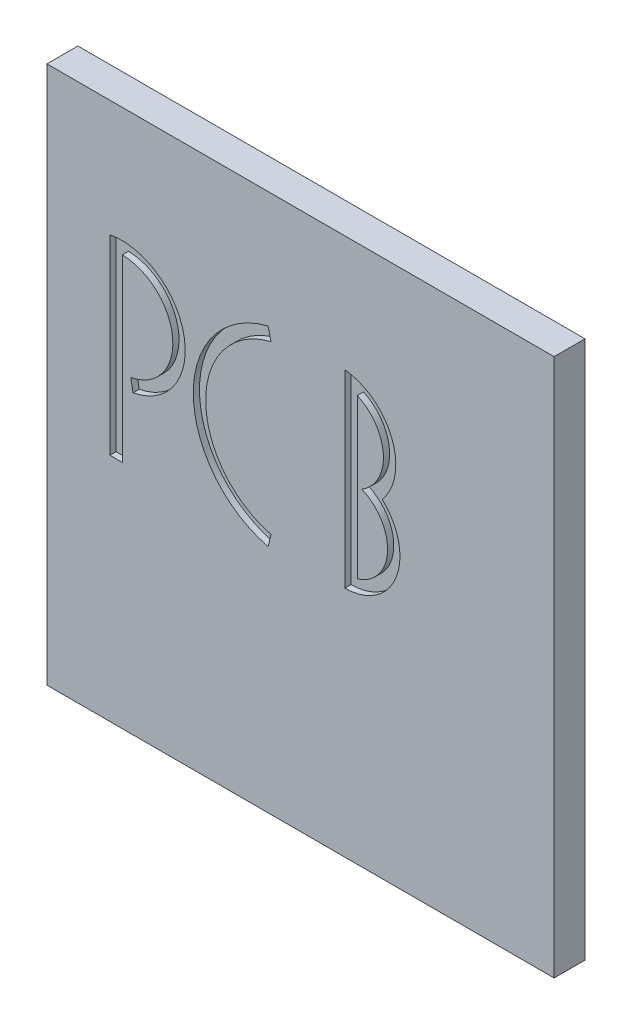
SolidWorks part; units mm, degrees
ref_plane "Front Plane" through (0, 0, 0) normal (0, 0, 1) x (1, 0, 0)
ref_plane "Top Plane" through (0, 0, 0) normal (0, 1, 0) x (1, 0, 0)
ref_plane "Right Plane" through (0, 0, 0) normal (1, 0, 0) x (0, 0, -1)
sketch "Esquisse1" plane through (0, 0, 0) normal (0, 0, 1) x (1, 0, 0)
  line L1 (41, 43.5) -> (-41, 43.5)
  line L2 (41, 43.5) -> (41, -43.5)
  line L3 (41, -43.5) -> (-41, -43.5)
  line L4 (-41, 43.5) -> (-41, -43.5)
  line L5 (41, 43.5) -> (-41, -43.5) construction
  line L6 (41, -43.5) -> (-41, 43.5) construction
  point P0 (0, 0)
  dimension "D1" = 87
  dimension "D2" = 82
extrude "Boss.-Extru.1" add sketch "Esquisse1" along normal blind 5
sketch "Esquisse2" plane through (0, 0, 5) normal (0, 0, 1) x (1, 0, 0)
  line L0 (-30.8207, 24.6686) -> (-30.8207, -6.2124)
  line L1 (-28.8207, 22.8387) -> (-28.8207, -6.2124)
  line L2 (-30.8207, -6.2124) -> (-28.8207, -6.2124)
  line L3 (-27.0812, 4.403) -> (-27.4441, 6.3698)
  line L4 (-5.2474, -6.2124) -> (-4.7684, -4.2706)
  line L5 (-5.2474, 24.6686) -> (-4.7684, 22.7268)
  line L6 (7.1774, 24.7531) -> (7.1774, -5.8222)
  line L7 (9.1774, 22.1557) -> (9.1774, -3.5259)
  arc A0 (-30.8207, 24.6686) -> (-27.0812, 4.403) centre (-28.951, 14.5358) cw
  arc A1 (-28.8207, 22.8387) -> (-27.4441, 6.3698) centre (-28.951, 14.5358) cw
  arc A2 (-5.2474, -6.2124) -> (-5.2474, 24.6686) centre (-1.4388, 9.2281) cw
  arc A3 (-4.7684, -4.2706) -> (-4.7684, 22.7268) centre (-1.4388, 9.2281) cw
  arc A4 (7.1774, -5.8222) -> (13.2089, 9.6183) centre (7.1774, 3.076) ccw
  arc A5 (13.2089, 9.6183) -> (7.1774, 24.7531) centre (6.18, 15.5864) ccw
  arc A6 (9.9162, 9.4073) -> (9.1774, 22.1557) centre (6.18, 15.5864) ccw
  arc A7 (9.1774, -3.5259) -> (9.9162, 9.4073) centre (7.1774, 3.076) ccw
  arc A8 (7.1774, -5.8222) -> (13.2089, 9.6183) centre (7.1774, 3.076) ccw construction
  point P24 (0, 0)
  point P25 (7.1774, 3.076)
  dimension "D1" = 2
  dimension "D2" = 2
  dimension "D3" = 2
extrude "Enlèv. mat.-Extru.1" cut sketch "Esquisse2" against normal blind 1
